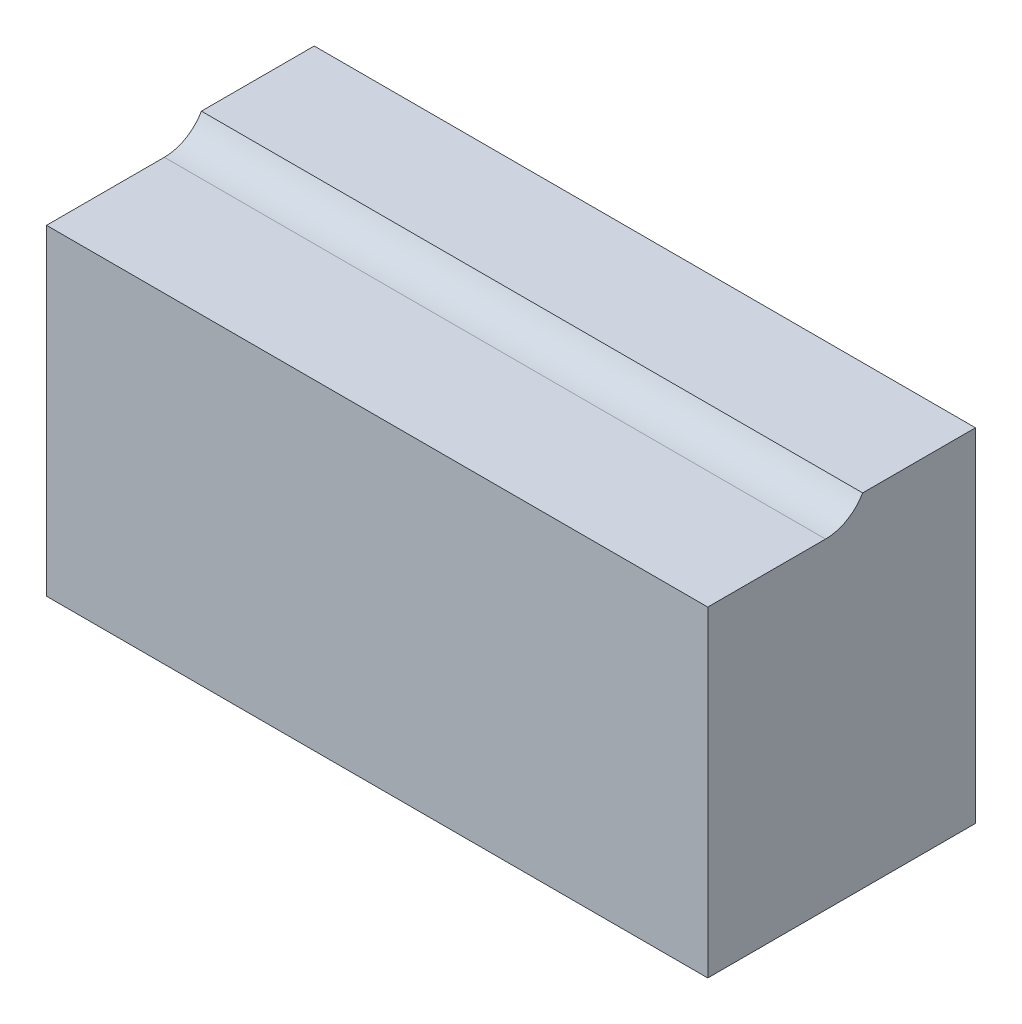
SolidWorks part; units mm, degrees
material "K110"
ref_plane "Front Plane" through (0, 0, 0) normal (0, 0, 1) x (1, 0, 0)
ref_plane "Top Plane" through (0, 0, 0) normal (0, 1, 0) x (1, 0, 0)
ref_plane "Right Plane" through (0, 0, 0) normal (1, 0, 0) x (0, 0, -1)
sketch "Sketch1" plane through (0, 0, 0) normal (0, 0, 1) x (1, 0, 0)
  line L1 (5.7154, -38) -> (67.4654, -38)
  line L2 (5.7154, -38) -> (5.7154, 0)
  line L3 (5.7154, 0) -> (67.4654, 0)
  line L4 (67.4654, -38) -> (67.4654, 0)
  dimension "D1" = 38
  dimension "D2" = 61.75
extrude "Boss-Extrude1" add sketch "Sketch1" along normal mid plane 25
sketch "Sketch2" plane through (67.4654, 0, 0) normal (1, 0, 0) x (0, 0, -1)
  line L0 (1.9641, -6) -> (12.5, -6)
  line L1 (12.5, -38) -> (12.5, 0) construction
  line L2 (12.5, -6) -> (12.5, 0)
  line L3 (12.5, 0) -> (-12.5, 0)
  line L4 (-12.5, 0) -> (-12.5, -8)
  line L5 (-12.5, -38) -> (-12.5, 0) construction
  line L6 (-12.5, -8) -> (-1.5, -8)
  line L7 (-12.5, -38) -> (12.5, -38) construction
  arc A1 (-1.5, -8) -> (1.9641, -6) centre (-1.5, -4) ccw
  dimension "D2" = 4
  dimension "D4" = 4
  dimension "D5" = 8
  dimension "D1" = 32
  dimension "D3" = 11
extrude "Cut-Extrude1" cut sketch "Sketch2" against normal up to next
hole_wizard "M6 Tapped Hole1" positions "Sketch5" profile "Sketch4" tap size "M6" standard "ISO"
sketch "Sketch5" plane through (0, -38, 0) normal (0, -1, 0) x (-1, 0, 0)
  line L0 (-67.4654, 0) -> (-5.7154, 0) construction
  line L1 (-67.4654, -12.5) -> (-67.4654, 12.5) construction
  line L2 (-5.7154, 12.5) -> (-5.7154, -12.5) construction
  line L4 (-36.5904, 12.5) -> (-36.5904, -12.5) construction
  line L5 (-67.4654, 12.5) -> (-5.7154, 12.5) construction
  line L6 (-5.7154, -12.5) -> (-67.4654, -12.5) construction
  point P0 (-15.5904, 0)
  point P2 (-57.5904, 0)
  dimension "D1" = 42
sketch "Sketch4" plane through (15.5904, -38, 0) normal (1, 0, 0) x (0, 0, -1)
  line L0 (0, 0) -> (0, 18.5022)
  line L1 (0, 18.5022) -> (2.5, 17)
  line L2 (2.5, 17) -> (2.5, 0)
  line L5 (2.5, 0) -> (0, 0)
  line L10 (0, 18.5022) -> (-2.5, 17) construction
  line L11 (0, -6.35) -> (0, 107.95) construction
  dimension "Tap Drill Dia." = 5
  dimension "Tap Drill Depth" = 17
  dimension "Drill Angle" = 118
cosmetic thread "Hole Thread1"
cosmetic thread "Hole Thread2"
